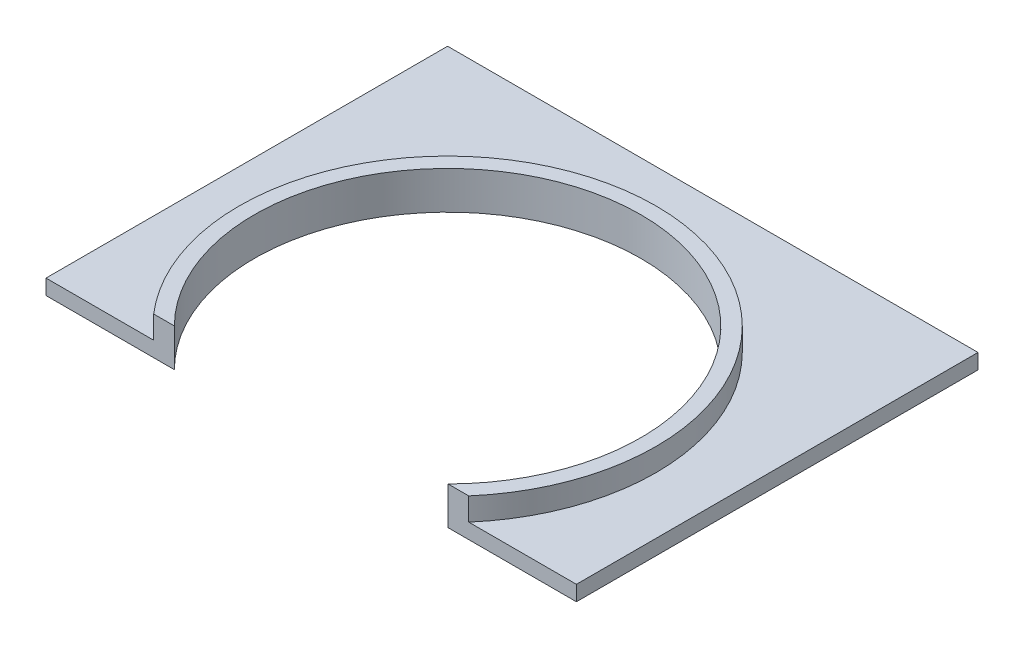
SolidWorks part; units mm, degrees
ref_plane "Alzado" through (0, 0, 0) normal (0, 0, 1) x (1, 0, 0)
ref_plane "Planta" through (0, 0, 0) normal (0, 1, 0) x (1, 0, 0)
ref_plane "Vista lateral" through (0, 0, 0) normal (1, 0, 0) x (0, 0, -1)
sketch "Croquis1" plane through (0, 0, 0) normal (0, 1, 0) x (1, 0, 0)
  line L1 (-35, 35) -> (35, 35)
  line L2 (-35, 35) -> (-35, -35)
  line L3 (-35, -35) -> (35, -35)
  line L4 (35, 35) -> (35, -35)
  line L5 (-35, 35) -> (35, -35) construction
  line L6 (-35, -35) -> (35, 35) construction
  circle A0 centre (0, 0) radius 25.5
  dimension "D1" = 51
  dimension "D2" = 70
  dimension "D3" = 70
extrude "Saliente-Extruir1" add sketch "Croquis1" along normal blind 2
sketch "Croquis2" plane through (0, 2, 0) normal (0, 1, 0) x (1, 0, 0)
  circle A0 centre (0, 0) radius 25.5 construction
  circle A1 centre (0, 0) radius 25.5
  circle A2 centre (0, 0) radius 27.5
  dimension "D1" = 2
extrude "Saliente-Extruir2" add sketch "Croquis2" along normal blind 3
sketch "Croquis3" plane through (0, 5, 0) normal (0, 1, 0) x (1, 0, 0)
  line L0 (-35, 35) -> (-35, -35) construction
  line L1 (-35, -35) -> (35, -35)
  line L2 (-35, -35) -> (-35, -18)
  line L3 (-35, -18) -> (35, -18)
  line L4 (35, -35) -> (35, -18)
  line L5 (35, -35) -> (35, 35) construction
  line L6 (-35, -35) -> (35, -35) construction
  point P8 (-35, -34.5228)
  dimension "D1" = 17
extrude "Cortar-Extruir1" cut sketch "Croquis3" against normal through all
